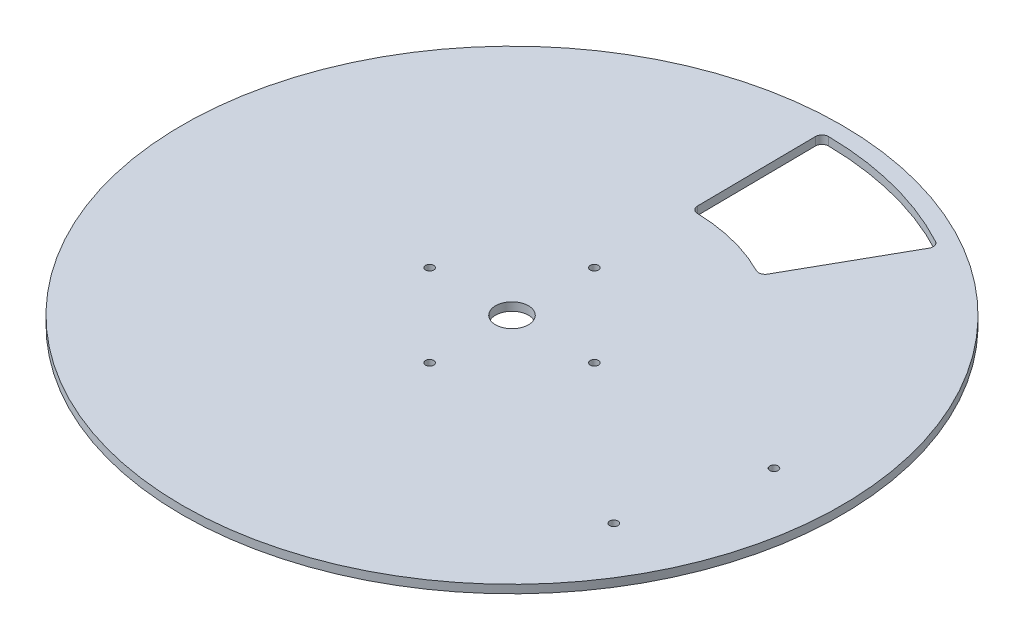
SolidWorks part; units mm, degrees
ref_plane "Front Plane" through (0, 0, 0) normal (0, 0, 1) x (1, 0, 0)
ref_plane "Top Plane" through (0, 0, 0) normal (0, 1, 0) x (1, 0, 0)
ref_plane "Right Plane" through (0, 0, 0) normal (1, 0, 0) x (0, 0, -1)
sketch "Sketch1" plane through (0, 0, 0) normal (0, 1, 0) x (1, 0, 0)
  circle A0 centre (0, 0) radius 127
  dimension "D1" = 254
extrude "Boss-Extrude1" add sketch "Sketch1" along normal blind 3.175
sketch "Sketch2" plane through (0, 3.175, 0) normal (0, 1, 0) x (1, 0, 0)
  circle A0 centre (0, 0) radius 6.35
  dimension "D1" = 12.7
extrude "Cut-Extrude1" cut sketch "Sketch2" against normal through all
sketch "Sketch3" plane through (0, 3.175, 0) normal (0, 1, 0) x (1, 0, 0)
  line L0 (0, 0) -> (-1.2681, 126.9937) construction
  line L1 (0, 0) -> (62.3986, 110.6138) construction
  line L2 (-0.6961, 69.7076) -> (-1.2047, 120.644)
  line L3 (34.3192, 60.8376) -> (59.2211, 104.981)
  circle A0 centre (0, 0) radius 69.85 construction
  circle A1 centre (0, 0) radius 120.65 construction
  circle A2 centre (0, 0) radius 127 construction
  arc A3 (-1.2047, 120.644) -> (59.2211, 104.981) centre (-0.0087, 0.869) cw
  arc A4 (-0.6961, 69.7076) -> (34.3192, 60.8376) centre (0.0105, -1.0515) cw
  dimension "D1" = 139.7
  dimension "D2" = 241.3
  dimension "D3" = 30
extrude "Cut-Extrude2" cut sketch "Sketch3" against normal through all
sketch "Sketch4" plane through (0, 3.175, 0) normal (0, 1, 0) x (1, 0, 0)
  line L0 (0, -31.75) -> (0, 0) construction
  circle A0 centre (0, -31.75) radius 1.5875
  dimension "D1" = 3.175
  dimension "D2" = 31.75
extrude "Cut-Extrude3" cut sketch "Sketch4" against normal through all
pattern_circular "CirPattern1" count 4 over 360 about axis through (0, 0, 0) along (0, 1, 0) of "Cut-Extrude3"
fillet "Fillet1" radius 2.54 4 edges at (-1.2047, 1.5875, -120.644) (59.2211, 1.5875, -104.981) (34.3192, 1.5875, -60.8376) (-0.6961, 1.5875, -69.7076)
sketch "Sketch5" plane through (0, 0, 0) normal (0, -1, 0) x (1, 0, 0)
  line L0 (17.3957, -67.5422) -> (0.0105, 1.0515) construction
  line L1 (0.0105, 1.0515) -> (134.8415, 35.2247) construction
  line L2 (89.062, 49.8249) -> (101.5427, 0.5819)
  arc A0 (1.7562, -69.6896) -> (32.17, -61.9811) centre (0.0105, 1.0515) ccw construction
  circle A1 centre (89.062, 49.8249) radius 1.5875
  circle A2 centre (101.5427, 0.5819) radius 1.5875
  point P12 (95.3023, 25.2034)
  dimension "D1" = 3.175
  dimension "D2" = 50.8
extrude "Cut-Extrude4" cut sketch "Sketch5" against normal through all contours A2 | A1
